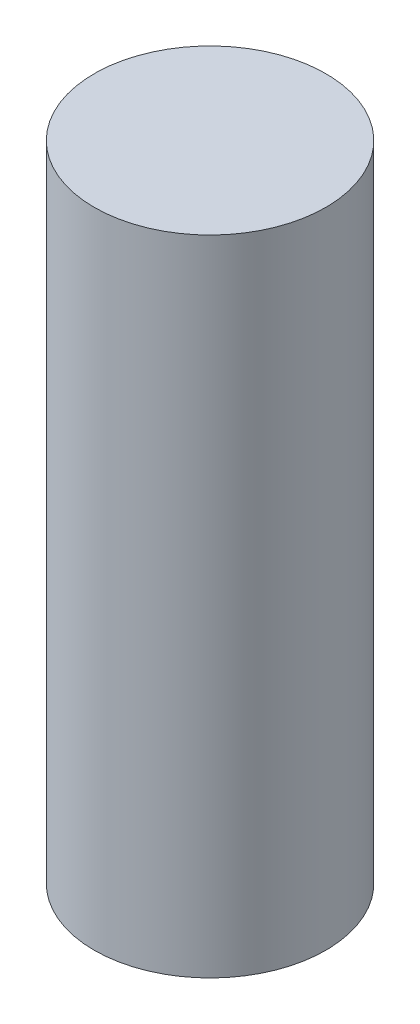
SolidWorks part; units mm, degrees
ref_plane "Piano frontale" through (0, 0, 0) normal (0, 0, 1) x (1, 0, 0)
ref_plane "Piano superiore" through (0, 0, 0) normal (0, 1, 0) x (1, 0, 0)
ref_plane "Piano destro" through (0, 0, 0) normal (1, 0, 0) x (0, 0, -1)
sketch "Schizzo1" plane through (0, 0, 0) normal (0, 1, 0) x (1, 0, 0)
  circle A0 centre (0, 0) radius 4.5
  dimension "D1" = 9
extrude "Estrusione-Estrusione1" add sketch "Schizzo1" along normal blind 25
